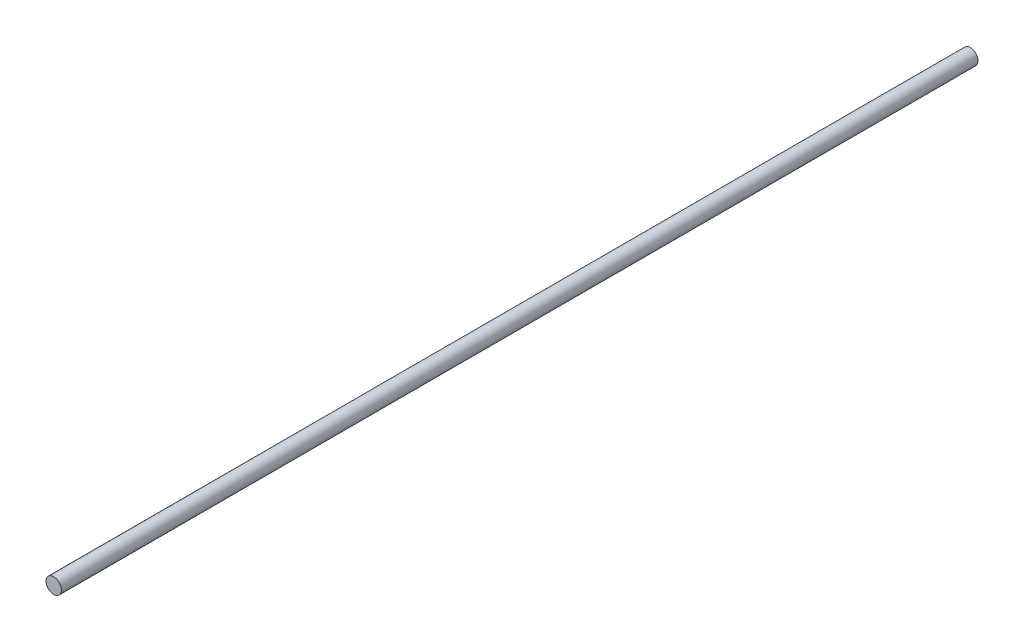
SolidWorks part; units mm, degrees
material "Hexcel AS4C (3000 Filaments)"
ref_plane "Front Plane" through (0, 0, 0) normal (0, 0, 1) x (1, 0, 0)
ref_plane "Top Plane" through (0, 0, 0) normal (0, 1, 0) x (1, 0, 0)
ref_plane "Right Plane" through (0, 0, 0) normal (1, 0, 0) x (0, 0, -1)
sketch "Sketch1" plane through (0, 0, 0) normal (0, 0, 1) x (1, 0, 0)
  circle A0 centre (0, 0) radius 0.8001
  dimension "D1" = 1.6002
extrude "Boss-Extrude1" add sketch "Sketch1" along normal blind 95.25
